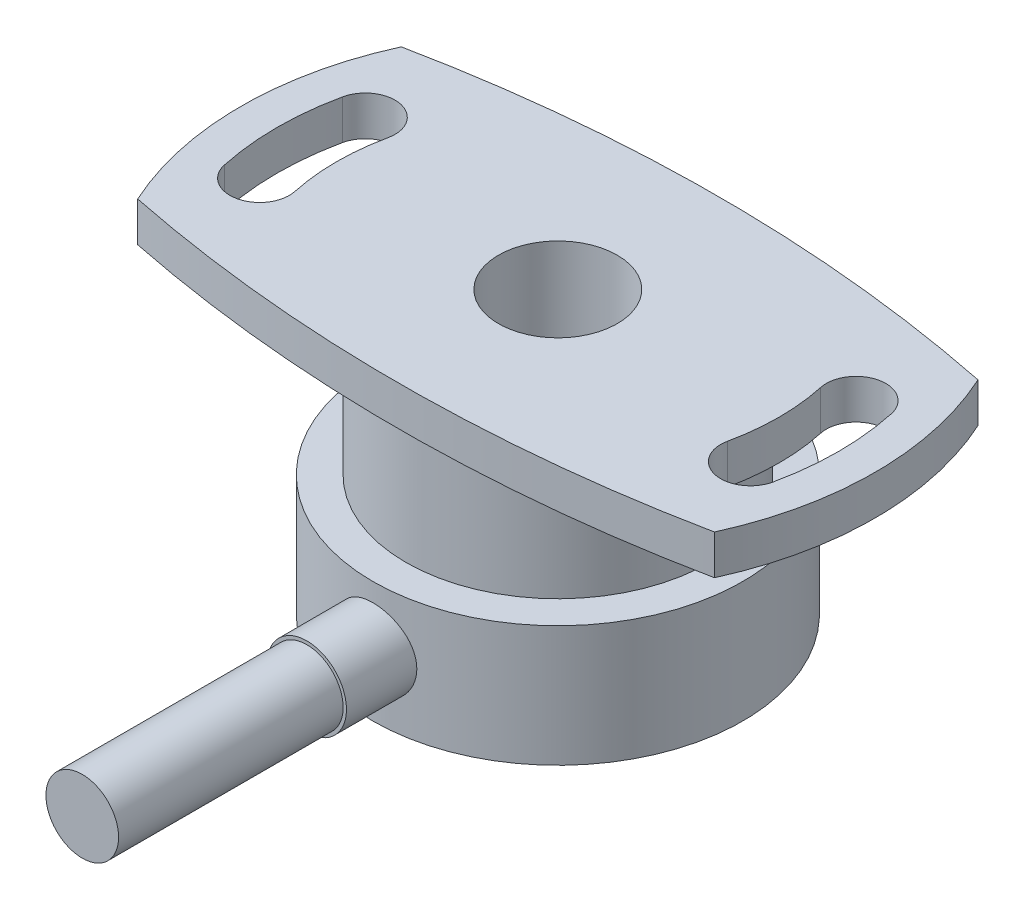
SolidWorks part; units mm, degrees
ref_plane "Front Plane" through (0, 0, 0) normal (0, 0, 1) x (1, 0, 0)
ref_plane "Top Plane" through (0, 0, 0) normal (0, 1, 0) x (1, 0, 0)
ref_plane "Right Plane" through (0, 0, 0) normal (1, 0, 0) x (0, 0, -1)
sketch "Sketch1" plane through (0, 0, 0) normal (0, 1, 0) x (1, 0, 0)
  circle A0 centre (0, 0) radius 14
  dimension "D1" = 28
extrude "Boss-Extrude1" add sketch "Sketch1" along normal blind 9.15
sketch "Sketch2" plane through (0, 9.15, 0) normal (0, 1, 0) x (1, 0, 0)
  circle A0 centre (0, 0) radius 11.5
  dimension "D1" = 23
extrude "Boss-Extrude2" add sketch "Sketch2" along normal blind 9.15
sketch "Sketch3" plane through (0, 18.3, 0) normal (0, 1, 0) x (1, 0, 0)
  line L1 (-20.6848, -12.1712) -> (20.6848, -12.1712)
  line L3 (-20.6848, 12.1712) -> (20.6848, 12.1712)
  line L5 (-20.6848, -12.1712) -> (20.6848, 12.1712) construction
  line L6 (-20.6848, 12.1712) -> (20.6848, -12.1712) construction
  arc A0 (-20.6848, 12.1712) -> (-20.6848, -12.1712) centre (0, 0) ccw
  arc A1 (20.6848, -12.1712) -> (20.6848, 12.1712) centre (0, 0) ccw
  point P0 (0, 0)
  point P2 (0, 0)
  point P9 (0, 0)
  point P11 (0, 0)
  point P13 (0, 0)
  dimension "D1" = 48
extrude "Boss-Extrude3" add sketch "Sketch3" along normal blind 3
sketch "Sketch4" plane through (0, 21.3, 0) normal (0, 1, 0) x (1, 0, 0)
  line L0 (-21.8287, -9.9755) -> (-21.8287, -23.8284)
  line L1 (-21.8287, -23.8284) -> (21.8287, -23.8284)
  line L2 (21.8287, -23.8284) -> (21.8287, -9.9755)
  line L3 (21.8287, 9.9755) -> (21.8287, 24.7952)
  line L4 (21.8287, 24.7952) -> (-21.8287, 24.7952)
  line L5 (-21.8287, 24.7952) -> (-21.8287, 9.9755)
  arc A0 (-21.8287, 9.9755) -> (21.8287, 9.9755) centre (0, -97.4323) cw
  arc A1 (-20.6848, 12.1712) -> (-20.6848, -12.1712) centre (0, 0) ccw construction
  arc A2 (20.6848, -12.1712) -> (20.6848, 12.1712) centre (0, 0) ccw construction
  arc A3 (-21.8287, -9.9755) -> (21.8287, -9.9755) centre (0, 97.4323) ccw
  dimension "D1" = 2.1957
extrude "Cut-Extrude1" cut sketch "Sketch4" against normal up to next
sketch "Sketch5" plane through (0, 21.3, 0) normal (0, 1, 0) x (1, 0, 0)
  circle A0 centre (0, 0) radius 19 construction
  dimension "D1" = 38
sketch "Sketch6" plane through (0, 21.3, 0) normal (0, 1, 0) x (1, 0, 0)
  line L0 (0, 0) -> (-18.5744, 3.999) construction
  line L1 (-19, 0) -> (0, 0) construction
  line L2 (0, 0) -> (-18.5744, -3.999) construction
  circle A0 centre (0, 0) radius 19 construction
  arc A1 (-18.5744, -3.999) -> (-18.5744, 3.999) centre (0, 0) cw construction
  arc A2 (-20.774, 4.4725) -> (-20.774, -4.4725) centre (0, 0) ccw
  arc A3 (-16.3748, 3.5254) -> (-16.3748, -3.5254) centre (0, 0) ccw
  arc A4 (-16.3748, 3.5254) -> (-20.774, 4.4725) centre (-18.5744, 3.999) ccw
  arc A5 (-20.774, -4.4725) -> (-16.3748, -3.5254) centre (-18.5744, -3.999) ccw
  point P8 (-19, 0)
  dimension "D2" = 2.25
  dimension "D1" = 12.15
extrude "Cut-Extrude2" cut sketch "Sketch6" against normal through all
mirror "Mirror1" about plane through (0, 0, 0) normal (1, 0, 0) of "Cut-Extrude2"
sketch "Sketch7" plane through (0, 0, 0) normal (0, 0, 1) x (1, 0, 0)
  circle A0 centre (0, 4.7625) radius 3
  dimension "D1" = 6
extrude "Boss-Extrude4" add sketch "Sketch7" along normal blind 19
sketch "Sketch8" plane through (0, 0, 19) normal (0, 0, 1) x (1, 0, 0)
  circle A0 centre (0, 4.7625) radius 2.75
  dimension "D1" = 5.5
extrude "Boss-Extrude5" add sketch "Sketch8" along normal blind 17
sketch "Sketch9" plane through (0, 0, 0) normal (0, -1, 0) x (1, 0, 0)
  circle A0 centre (0, 0) radius 4.495
  dimension "D1" = 8.99
extrude "Cut-Extrude3" cut sketch "Sketch9" against normal through all
